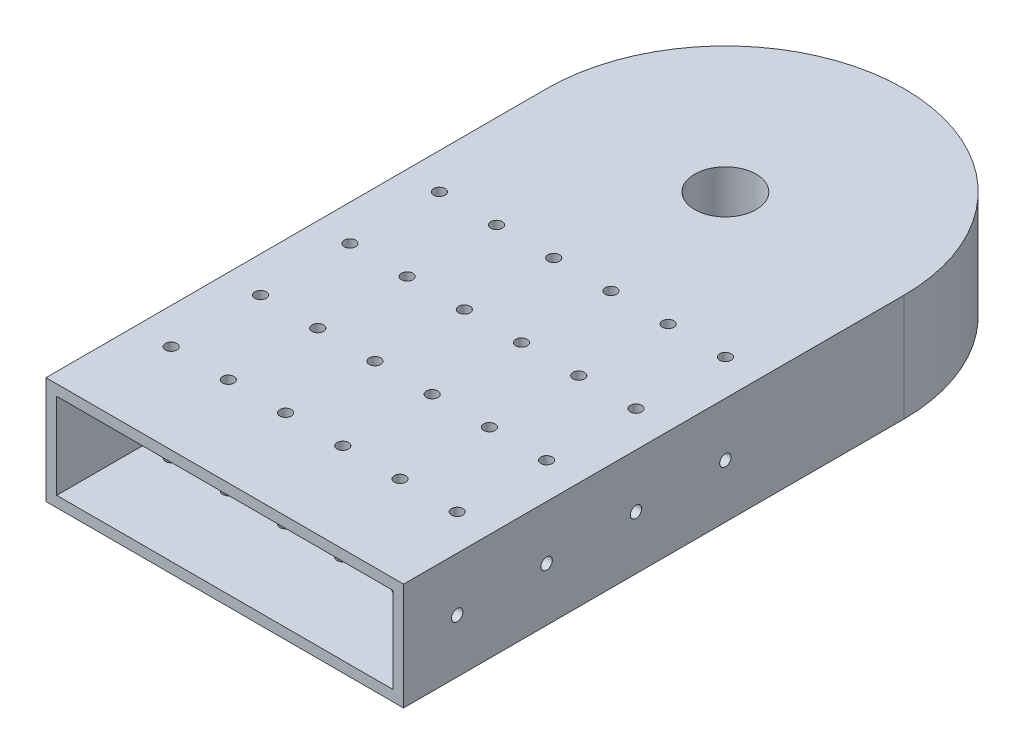
SolidWorks part; units mm, degrees
ref_plane "前视基准面" through (0, 0, 0) normal (0, 0, 1) x (1, 0, 0)
ref_plane "上视基准面" through (0, 0, 0) normal (0, 1, 0) x (1, 0, 0)
ref_plane "右视基准面" through (0, 0, 0) normal (1, 0, 0) x (0, 0, -1)
other "Configuration Table"
sketch "Sketch1" plane through (0, 0, 0) normal (0, 1, 0) x (1, 0, 0)
  line L0 (-50, 0) -> (-50, -140)
  line L1 (50, 0) -> (50, -140)
  line L2 (-50, -140) -> (50, -140)
  arc A0 (50, 0) -> (-50, 0) centre (0, 0) ccw
  circle A1 centre (0, 0) radius 8.6
  dimension "D1" = 50
  dimension "D3" = 17.2
  dimension "D2" = 140
extrude "Boss-Extrude1" add sketch "Sketch1" along normal blind 30
shell "Shell1" thickness 3
sketch "Sketch2" plane through (50, 0, 0) normal (1, 0, 0) x (0, 0, -1)
  line L0 (-140, 15) -> (-40, 15) construction
  line L1 (-140, 30) -> (-140, 0) construction
  circle A0 centre (-125, 15) radius 1.6
  circle A1 centre (-100, 15) radius 1.6
  circle A2 centre (-75, 15) radius 1.6
  circle A3 centre (-50, 15) radius 1.6
  dimension "D2" = 3.2
  dimension "D3" = 3.2
  dimension "D4" = 15
  dimension "D5" = 25
  dimension "D1" = 100
  dimension "D6" = 3
extrude "Cut-Extrude1" cut sketch "Sketch2" against normal blind 143
sketch "Sketch3" plane through (0, 30, 0) normal (0, 1, 0) x (1, 0, 0)
  line L0 (-50, -140) -> (-50, -115) construction
  line L1 (-50, 0) -> (-50, -140) construction
  line L2 (-50, -115) -> (50, -115) construction
  line L3 (50, -140) -> (50, 0) construction
  circle A0 centre (-40, -115) radius 1.6
  circle A1 centre (-24, -115) radius 1.6
  circle A2 centre (-8, -115) radius 1.6
  circle A3 centre (8, -115) radius 1.6
  circle A4 centre (24, -115) radius 1.6
  circle A5 centre (40, -115) radius 1.6
  circle A6 centre (-40, -90) radius 1.6
  circle A7 centre (-24, -90) radius 1.6
  circle A8 centre (-8, -90) radius 1.6
  circle A9 centre (8, -90) radius 1.6
  circle A10 centre (24, -90) radius 1.6
  circle A11 centre (40, -90) radius 1.6
  circle A12 centre (-40, -65) radius 1.6
  circle A13 centre (-24, -65) radius 1.6
  circle A14 centre (-8, -65) radius 1.6
  circle A15 centre (8, -65) radius 1.6
  circle A16 centre (24, -65) radius 1.6
  circle A17 centre (40, -65) radius 1.6
  circle A18 centre (-40, -40) radius 1.6
  circle A19 centre (-24, -40) radius 1.6
  circle A20 centre (-8, -40) radius 1.6
  circle A21 centre (8, -40) radius 1.6
  circle A22 centre (24, -40) radius 1.6
  circle A23 centre (40, -40) radius 1.6
  dimension "D2" = 10
  dimension "D3" = 3.2
  dimension "D1" = 25
  dimension "D4" = 6
  dimension "D5" = 4
extrude "Cut-Extrude2" cut sketch "Sketch3" against normal blind 47
